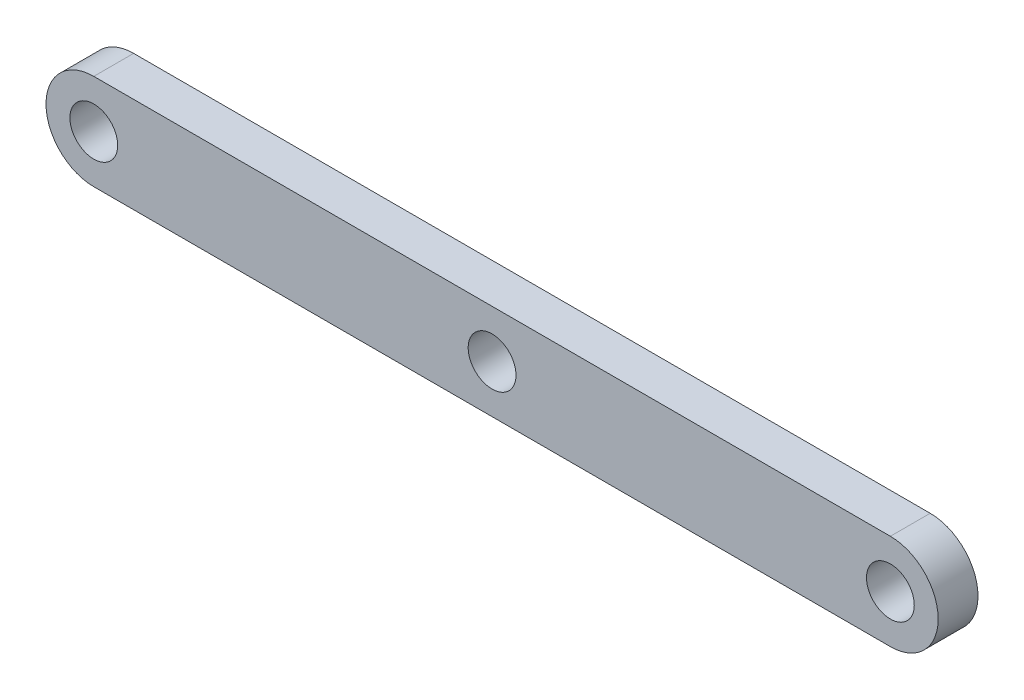
SolidWorks part; units mm, degrees
material "Acrylic (Medium-high impact)"
ref_plane "Front Plane" through (0, 0, 0) normal (0, 0, 1) x (1, 0, 0)
ref_plane "Top Plane" through (0, 0, 0) normal (0, 1, 0) x (1, 0, 0)
ref_plane "Right Plane" through (0, 0, 0) normal (1, 0, 0) x (0, 0, -1)
sketch "Sketch1" plane through (0, 0, 0) normal (0, 0, 1) x (1, 0, 0)
  line L0 (-50, 0) -> (50, 0) construction
  line L1 (-50, 6) -> (50, 6)
  line L2 (-50, -6) -> (50, -6)
  arc A0 (-50, 6) -> (-50, -6) centre (-50, 0) ccw
  arc A1 (50, -6) -> (50, 6) centre (50, 0) ccw
  circle A2 centre (-50, 0) radius 3
  circle A3 centre (50, 0) radius 3
  circle A4 centre (0, 0) radius 3
  point P2 (0, 0)
  dimension "D3" = 6
  dimension "D1" = 100
  dimension "D2" = 12
extrude "Boss-Extrude1" add sketch "Sketch1" along normal mid plane 5
